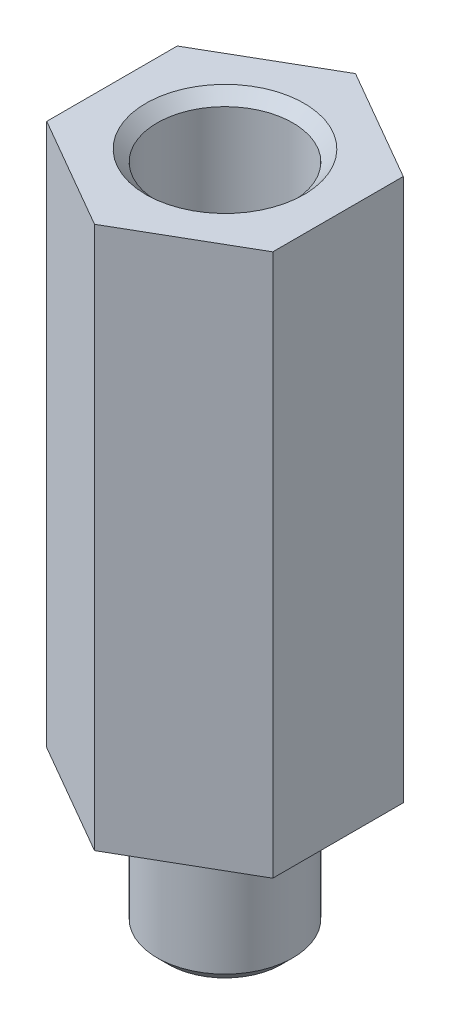
SolidWorks part; units mm, degrees
material "Brass"
ref_plane "Front Plane" through (0, 0, 0) normal (0, 0, 1) x (1, 0, 0)
ref_plane "Top Plane" through (0, 0, 0) normal (0, 1, 0) x (1, 0, 0)
ref_plane "Right Plane" through (0, 0, 0) normal (1, 0, 0) x (0, 0, -1)
sketch "Sketch1" plane through (0, 0, 0) normal (0, 1, 0) x (1, 0, 0)
  line L1 (0, 2.8868) -> (-2.5, 1.4434)
  line L2 (-2.5, 1.4434) -> (-2.5, -1.4434)
  line L3 (-2.5, -1.4434) -> (0, -2.8868)
  line L4 (0, -2.8868) -> (2.5, -1.4434)
  line L5 (2.5, -1.4434) -> (2.5, 1.4434)
  line L6 (2.5, 1.4434) -> (0, 2.8868)
  circle A0 centre (0, 0) radius 2.5 construction
  dimension "D1" = 5
extrude "Boss-Extrude1" add sketch "Sketch1" along normal mid plane 12
sketch "Sketch2" plane through (0, 6, 0) normal (0, 1, 0) x (1, 0, 0)
  circle A0 centre (0, 0) radius 1.5
  dimension "D1" = 3
extrude "Cut-Extrude1" cut sketch "Sketch2" against normal blind 8
sketch "Sketch3" plane through (0, -6, 0) normal (0, -1, 0) x (1, 0, 0)
  circle A0 centre (0, 0) radius 1.5
  dimension "D1" = 3
extrude "Boss-Extrude2" add sketch "Sketch3" along normal blind 3
chamfer "Chamfer2" distance 0.25 angle 45 2 edges at (0, 6, 1.5) (0, -9, -1.5)
